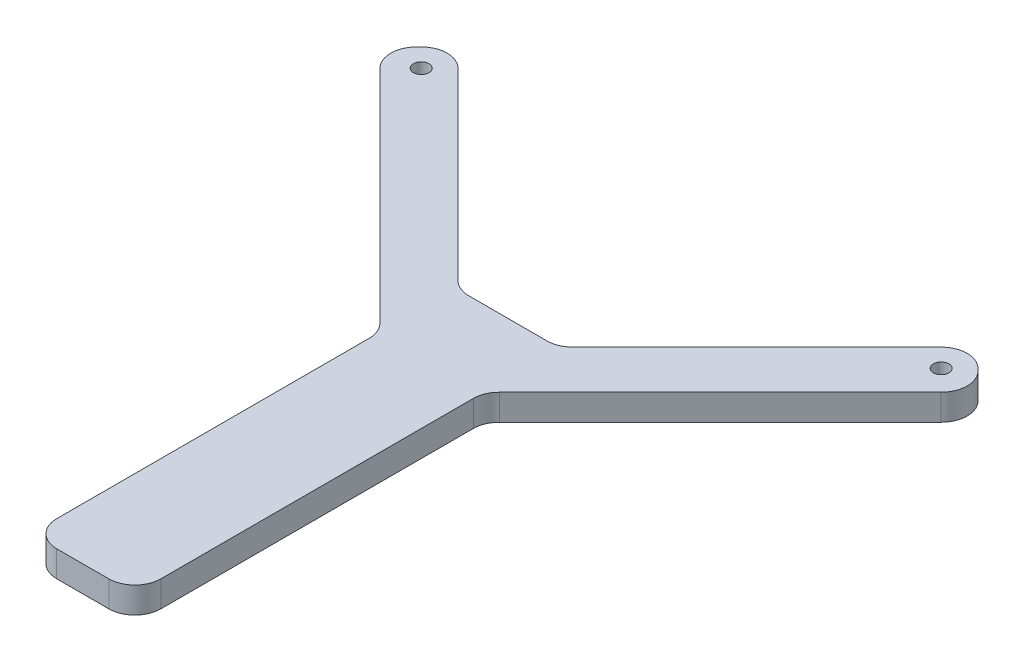
SolidWorks part; units mm, degrees
material "1060 Alloy"
ref_plane "Front Plane" through (0, 0, 0) normal (0, 0, 1) x (1, 0, 0)
ref_plane "Top Plane" through (0, 0, 0) normal (0, 1, 0) x (1, 0, 0)
ref_plane "Right Plane" through (0, 0, 0) normal (1, 0, 0) x (0, 0, -1)
sketch "Sketch1" plane through (0, 0, 0) normal (0, 1, 0) x (1, 0, 0)
  line L0 (-3.7197, 3.7197) -> (-111.4828, 111.4828)
  line L1 (-111.4828, 129.4433) -> (-110.3933, 130.5328)
  line L2 (-92.4328, 130.5328) -> (-2.6303, 40.7303)
  line L3 (6.35, 37.0105) -> (44.45, 37.0105)
  line L4 (53.4303, 40.7303) -> (143.2328, 130.5328)
  line L5 (161.1933, 130.5328) -> (162.2828, 129.4433)
  line L6 (162.2828, 111.4828) -> (54.5197, 3.7197)
  line L7 (0, -5.2605) -> (0, -157.6605)
  line L8 (12.7, -170.3605) -> (38.1, -170.3605)
  line L9 (50.8, -157.6605) -> (50.8, -5.2605)
  arc A0 (44.45, 37.0105) -> (53.4303, 40.7303) centre (44.45, 49.7105) ccw
  arc A1 (143.2328, 130.5328) -> (161.1933, 130.5328) centre (152.2131, 121.5526) cw
  arc A2 (162.2828, 129.4433) -> (162.2828, 111.4828) centre (153.3026, 120.4631) cw
  arc A3 (54.5197, 3.7197) -> (50.8, -5.2605) centre (63.5, -5.2605) ccw
  arc A4 (50.8, -157.6605) -> (38.1, -170.3605) centre (38.1, -157.6605) cw
  arc A5 (12.7, -170.3605) -> (0, -157.6605) centre (12.7, -157.6605) cw
  arc A6 (0, -5.2605) -> (-3.7197, 3.7197) centre (-12.7, -5.2605) ccw
  arc A7 (6.35, 37.0105) -> (-2.6303, 40.7303) centre (6.35, 49.7105) cw
  arc A8 (-111.4828, 111.4828) -> (-111.4828, 129.4433) centre (-102.5026, 120.4631) cw
  arc A9 (-92.4328, 130.5328) -> (-110.3933, 130.5328) centre (-101.4131, 121.5526) ccw
  circle A10 centre (152.2131, 121.5526) radius 3.81
  circle A11 centre (-101.4131, 121.5526) radius 3.81
  point P25 (0, 0)
  dimension "D1" = 12.7
  dimension "D10" = 7.62
  dimension "D2" = 152.4
  dimension "D3" = 152.4
  dimension "D4" = 152.4
  dimension "D5" = 152.4
  dimension "D6" = 38.1
  dimension "D7" = 127
  dimension "D8" = 127
  dimension "D9" = 25.4
extrude "Boss-Extrude1" add sketch "Sketch1" along normal blind 12.7
